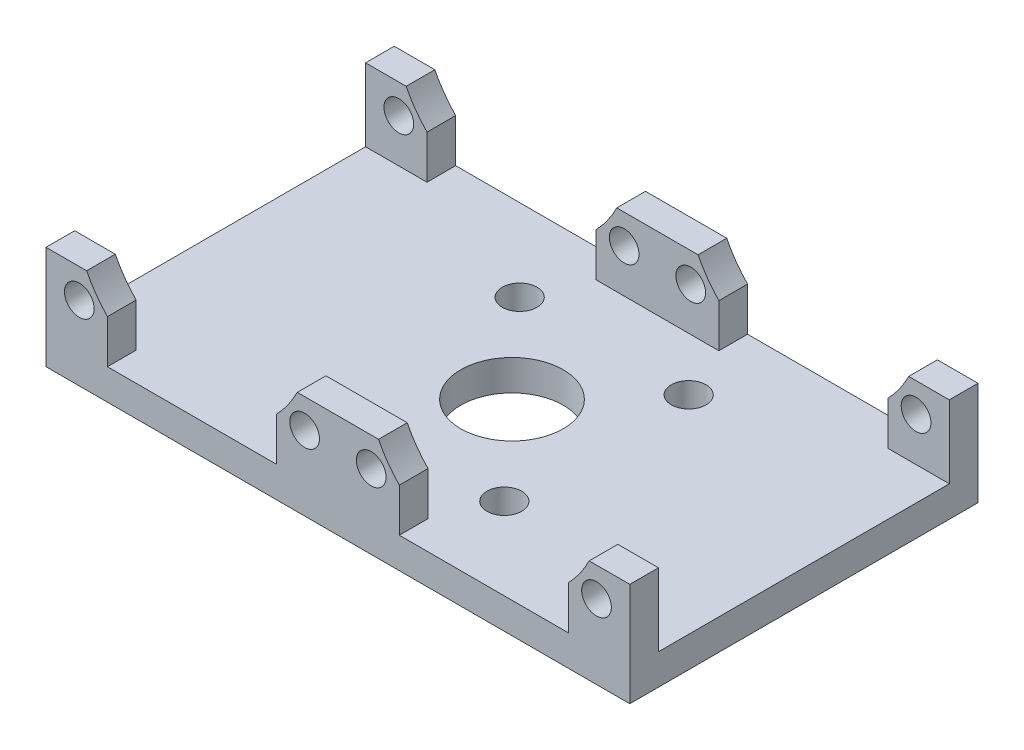
SolidWorks part; units mm, degrees
ref_plane "Front Plane" through (0, 0, 0) normal (0, 0, 1) x (1, 0, 0)
ref_plane "Top Plane" through (0, 0, 0) normal (0, 1, 0) x (1, 0, 0)
ref_plane "Right Plane" through (0, 0, 0) normal (1, 0, 0) x (0, 0, -1)
sketch "Sketch1" plane through (0, 0, 0) normal (0, 1, 0) x (1, 0, 0)
  line L1 (-28.5, 17) -> (28.5, 17)
  line L2 (-28.5, 17) -> (-28.5, -17)
  line L3 (-28.5, -17) -> (28.5, -17)
  line L4 (28.5, 17) -> (28.5, -17)
  line L5 (-28.5, 17) -> (28.5, -17) construction
  line L6 (-28.5, -17) -> (28.5, 17) construction
  circle A0 centre (0, 0) radius 5
  circle A1 centre (-8.25, 9) radius 1.7
  circle A5 centre (8.25, 9) radius 1.7
  circle A6 centre (8.25, -9) radius 1.7
  circle A7 centre (-8.25, -9) radius 1.7
  point P0 (0, 0)
  dimension "D3" = 10
  dimension "D4" = 3.4
  dimension "D5" = 8.25
  dimension "D8" = 2
  dimension "D6" = 9
  dimension "D1" = 57
  dimension "D2" = 34
  dimension "D7" = 2
extrude "Boss-Extrude1" add sketch "Sketch1" along normal blind 3
ref_plane "Plane2" through (0, 0, 0) normal (0, 0, 1) x (1, 0, 0)
sketch "Sketch6" plane through (0, 0, 17) normal (0, 0, 1) x (1, 0, 0)
  line L0 (-22.5, 3) -> (-6, 3) construction
  line L1 (-28.5, 3) -> (-22.5, 3)
  line L2 (-28.5, 3) -> (-28.5, 10.1)
  line L3 (-28.5, 10.1) -> (-22.5, 10.1)
  line L4 (-22.5, 3) -> (-22.5, 10.1)
  line L5 (-28.5, 3) -> (28.5, 3) construction
  line L6 (22.5, 3) -> (6, 3) construction
  line L7 (-6, 3) -> (0, 3)
  line L8 (-6, 3) -> (-6, 10.1)
  line L9 (-6, 10.1) -> (0, 10.1)
  line L10 (0, 3) -> (0, 10.1)
  line L11 (0, 3) -> (6, 3)
  line L12 (0, 3) -> (0, 10.1)
  line L13 (0, 10.1) -> (6, 10.1)
  line L14 (6, 3) -> (6, 10.1)
  line L15 (28.5, 3) -> (22.5, 3)
  line L16 (28.5, 3) -> (28.5, 10.1)
  line L17 (28.5, 10.1) -> (22.5, 10.1)
  line L18 (22.5, 3) -> (22.5, 10.1)
  line L19 (14.25, 3) -> (14.25, 12.5555) construction
  line L20 (-6, 3) -> (-22.5, 3) construction
  line L21 (-14.25, 3) -> (-14.25, 11.3572) construction
  circle A1 centre (-3.25, 7.25) radius 1.45
  circle A2 centre (3.25, 7.25) radius 1.45
  circle A3 centre (25.25, 7.25) radius 1.45
  circle A4 centre (-25.25, 7.25) radius 1.45
  circle A5 centre (14.25, 15.25) radius 11.5
  circle A6 centre (-14.25, 15.25) radius 11.5
  line M16 (28.5, 3) -> (-28.5, 3)
  dimension "D9" = 2.9
  dimension "D10" = 3.25
  dimension "D11" = 2.85
  dimension "D12" = 2.85
  dimension "D13" = 3.25
  dimension "D14" = 12.25
  dimension "D15" = 12.25
  dimension "D1" = 6
  dimension "D2" = 7.1
  dimension "D3" = 16.5
  dimension "D4" = 6
  dimension "D5" = 7.1
  dimension "D6" = 6
  dimension "D7" = 6
  dimension "D8" = 7.1
extrude "Boss-Extrude3" add sketch "Sketch6" against normal blind 2.8 contours A5 L18 L16 L17 A3 M16 | A5 L13 L10 L14 A2 M16 | A6 L8 L10 L9 A1 M16 | A6 L3 L2 L4 A4 M16
mirror "Mirror2" about plane through (0, 0, 0) normal (0, 0, 1) of "Boss-Extrude3"
